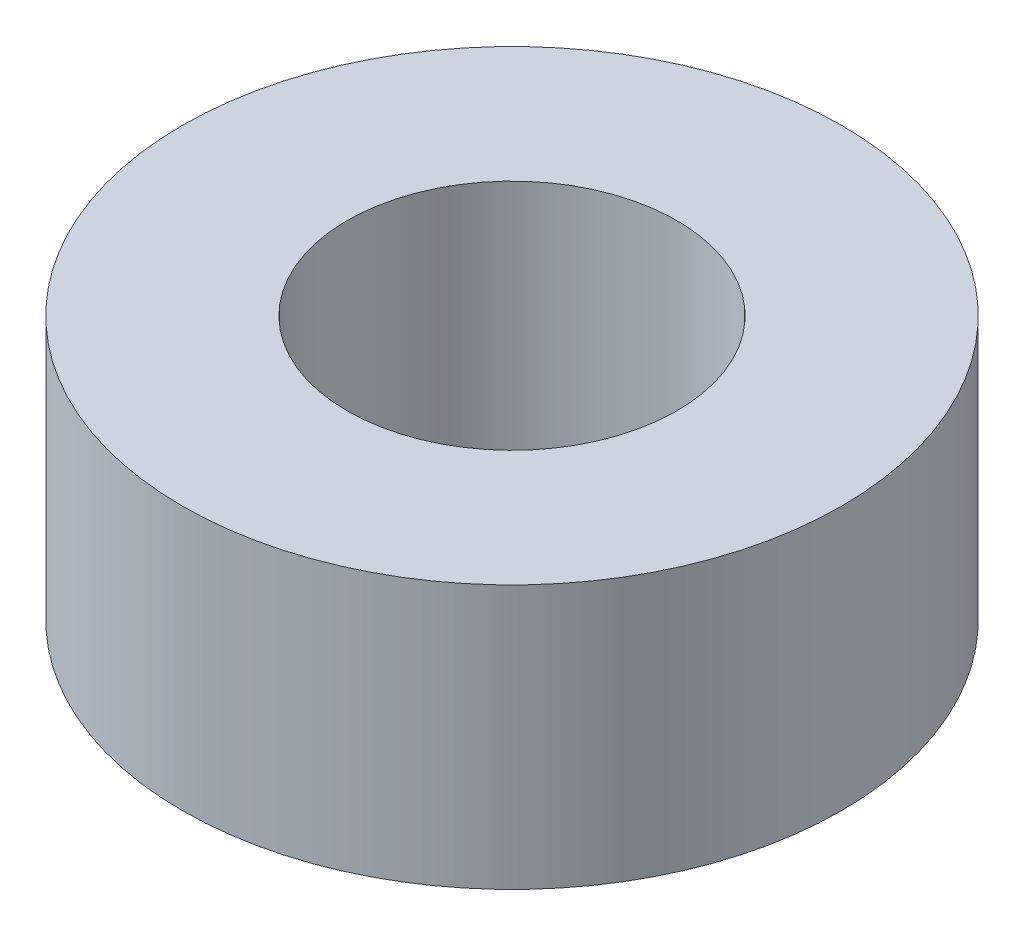
SolidWorks part; units mm, degrees
ref_plane "Front Plane" through (0, 0, 0) normal (0, 0, 1) x (1, 0, 0)
ref_plane "Top Plane" through (0, 0, 0) normal (0, 1, 0) x (1, 0, 0)
ref_plane "Right Plane" through (0, 0, 0) normal (1, 0, 0) x (0, 0, -1)
sketch "Sketch1" plane through (0, 0, 0) normal (0, 1, 0) x (1, 0, 0)
  circle A0 centre (0, 0) radius 2.5
  circle A1 centre (0, 0) radius 5
  dimension "D1" = 10
  dimension "D2" = 5
extrude "Boss-Extrude1" add sketch "Sketch1" along normal blind 4
